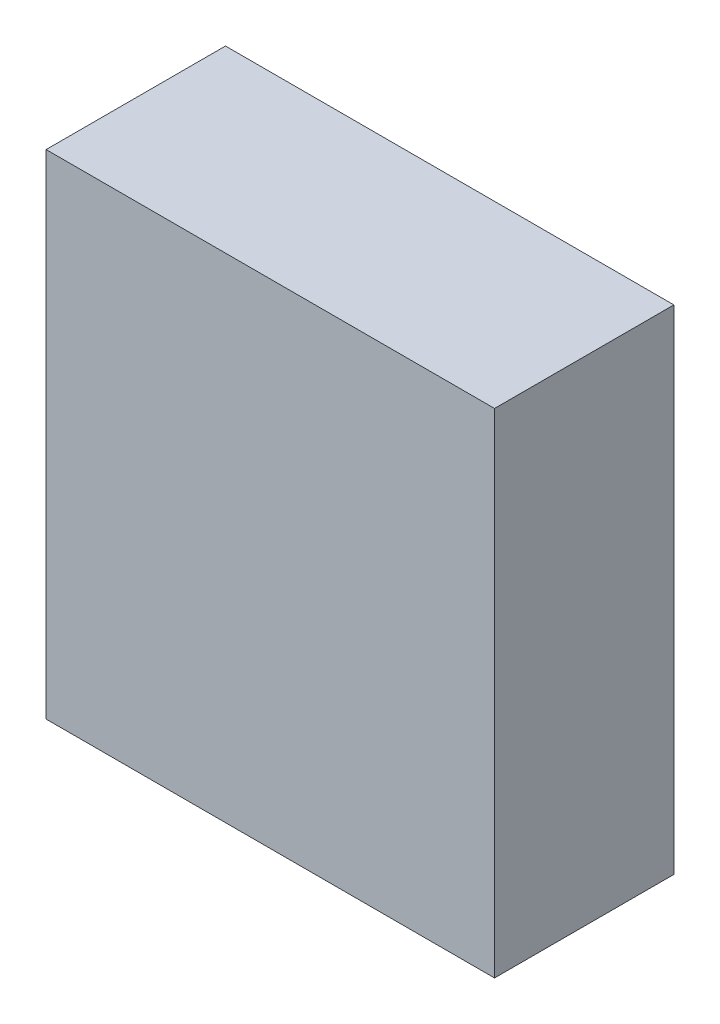
SolidWorks part; units mm, degrees
ref_plane "Front Plane" through (0, 0, 0) normal (0, 0, 1) x (1, 0, 0)
ref_plane "Top Plane" through (0, 0, 0) normal (0, 1, 0) x (1, 0, 0)
ref_plane "Right Plane" through (0, 0, 0) normal (1, 0, 0) x (0, 0, -1)
other "Configuration Table"
sketch "Sketch1" plane through (0, 0, 0) normal (0, 0, 1) x (1, 0, 0)
  line L1 (240, 560) -> (340, 560)
  line L2 (240, 560) -> (240, 670)
  line L3 (240, 670) -> (340, 670)
  line L4 (340, 560) -> (340, 670)
extrude "TOPPING_arka_duvar_pano_guc_kaynagi_1" add sketch "Sketch1" against normal blind 40 from offset 736 separate body
